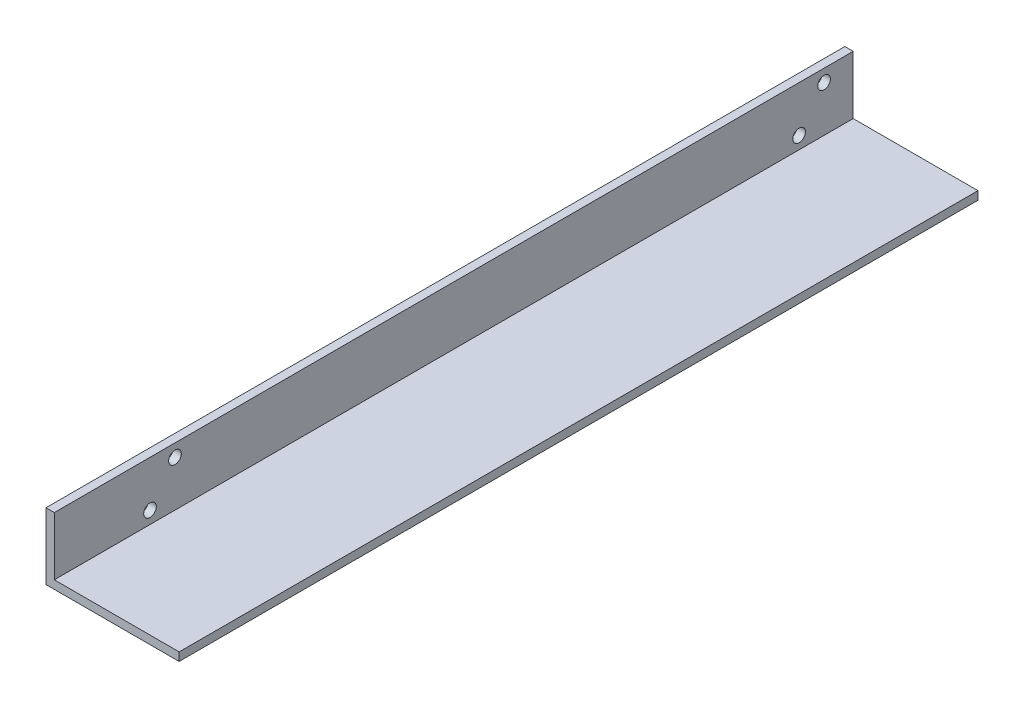
SolidWorks part; units mm, degrees
ref_plane "Front Plane" through (0, 0, 0) normal (0, 0, 1) x (1, 0, 0)
ref_plane "Top Plane" through (0, 0, 0) normal (0, 1, 0) x (1, 0, 0)
ref_plane "Right Plane" through (0, 0, 0) normal (1, 0, 0) x (0, 0, -1)
sketch "Sketch1" plane through (0, 0, 0) normal (0, 0, 1) x (1, 0, 0)
  line L0 (3.175, 3.175) -> (3.175, 25.4)
  line L1 (0, 0) -> (50.8, 0)
  line L2 (0, 0) -> (0, 25.4)
  line L5 (3.175, 3.175) -> (50.8, 3.175)
  line L6 (0, 25.4) -> (3.175, 25.4)
  line L7 (50.8, 0) -> (50.8, 3.175)
  dimension "D1" = 25.4
  dimension "D2" = 50.8
  dimension "D3" = 3.175
extrude "Boss-Extrude1" add sketch "Sketch1" along normal blind 304.8
sketch "Sketch2" plane through (0, 0, 0) normal (-1, 0, 0) x (0, 0, 1)
  circle A0 centre (258.7625, 20.6375) radius 2.413 construction
  circle A1 centre (258.7625, 20.6375) radius 2.413
  circle A2 centre (268.2875, 7.9375) radius 2.413 construction
  circle A3 centre (268.2875, 7.9375) radius 2.413
  circle A4 centre (11.1125, 20.6375) radius 2.413 construction
  circle A5 centre (11.1125, 20.6375) radius 2.413
  circle A6 centre (20.6375, 7.9375) radius 2.413 construction
  circle A7 centre (20.6375, 7.9375) radius 2.413
extrude "Cut-Extrude1" cut sketch "Sketch2" against normal up to next
